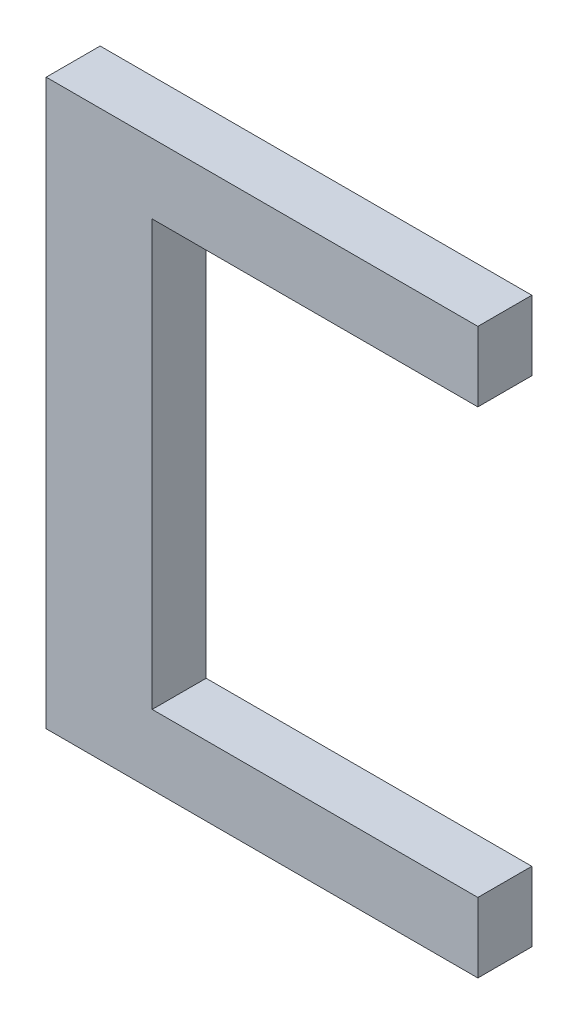
SolidWorks part; units mm, degrees
ref_plane "Front Plane" through (0, 0, 0) normal (0, 0, 1) x (1, 0, 0)
ref_plane "Top Plane" through (0, 0, 0) normal (0, 1, 0) x (1, 0, 0)
ref_plane "Right Plane" through (0, 0, 0) normal (1, 0, 0) x (0, 0, -1)
sketch "Sketch1" plane through (0, 0, 0) normal (0, 0, 1) x (1, 0, 0)
  line L0 (24.0041, 31.382) -> (0, 31.382)
  line L1 (0, 31.382) -> (0, 0)
  line L2 (0, 0) -> (24.0041, 0)
  line L3 (24.0041, 0) -> (24.0041, 3.88)
  line L4 (24.0041, 3.88) -> (5.895, 3.88)
  line L5 (5.895, 3.88) -> (5.895, 27.502)
  line L6 (5.895, 27.502) -> (24.0041, 27.502)
  line L7 (24.0041, 27.502) -> (24.0041, 31.382)
  dimension "D2" = 23.622
  dimension "D3" = 24.0041
  dimension "D4" = 18.1091
  dimension "D5" = 3.88
extrude "Boss-Extrude1" add sketch "Sketch1" along normal blind 3 contours L6 L7 L0 L1 L2 L3 L4 L5
